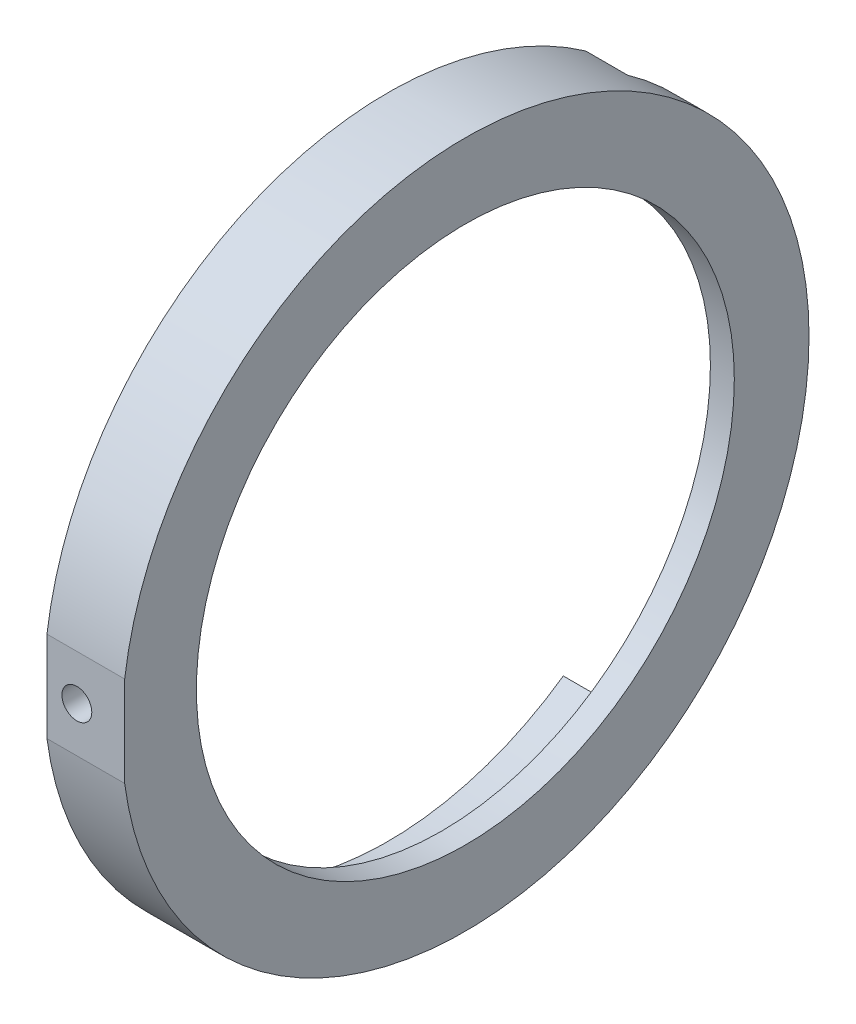
SolidWorks part; units mm, degrees
material "Stainless Steel (ferritic)"
ref_plane "Front Plane" through (0, 0, 0) normal (0, 0, 1) x (1, 0, 0)
ref_plane "Top Plane" through (0, 0, 0) normal (0, 1, 0) x (1, 0, 0)
ref_plane "Right Plane" through (0, 0, 0) normal (1, 0, 0) x (0, 0, -1)
sketch "Sketch1" plane through (0, 0, 0) normal (1, 0, 0) x (0, 0, -1)
  line L0 (-57, 7.5664) -> (-57, -7.5664)
  arc A0 (-57, -7.5664) -> (-57, 7.5664) centre (0, 0) ccw
  dimension "D1" = 115
  dimension "D2" = 57
extrude "Boss-Extrude1" add sketch "Sketch1" along normal blind 6
sketch "Sketch2" plane through (0, 0, 0) normal (-1, 0, 0) x (0, 0, 1)
  line L0 (-33.1248, -47) -> (-33.1248, 47)
  line L1 (-33.1248, 47) -> (-29.3802, 41.687)
  line L2 (-33.1248, -47) -> (-29.3802, -41.687)
  arc A1 (57, 7.5664) -> (57, -7.5664) centre (0, 0) ccw construction
  arc A2 (50.5565, 6.711) -> (50.5565, -6.711) centre (0, 0) ccw
  circle A3 centre (0, 0) radius 51
  arc M2 (57, 7.5664) -> (57, -7.5664) centre (0, 0) ccw
  line M3 (57, -7.5664) -> (57, 7.5664)
  dimension "D2" = 94
  dimension "D1" = 6.5
extrude "Boss-Extrude2" add sketch "Sketch2" along normal blind 7 contours A3 L2 L1 M2 M3
sketch "Sketch3" plane through (0, 0, 57) normal (0, 0, 1) x (1, 0, 0)
  line L0 (-7, -7.5664) -> (-7, 7.5664) construction
  circle A0 centre (-2, 0) radius 2.5
  point P4 (-7, 0)
  dimension "D1" = 5
  dimension "D2" = 5
extrude "Cut-Extrude1" cut sketch "Sketch3" against normal blind 7
sketch "Sketch4" plane through (6, 0, 0) normal (1, 0, 0) x (0, 0, -1)
  arc A2 (-44.6087, 5.9215) -> (-44.6071, -5.9338) centre (0, 0) ccw
  arc A3 (-44.6087, -5.9215) -> (-44.6087, 5.9215) centre (0, 0) ccw
  arc A4 (-44.6087, -5.9215) -> (-44.6087, 5.9215) centre (0, 0) ccw
  dimension "D1" = 12.5
extrude "Cut-Extrude2" cut sketch "Sketch4" against normal up to next contours A2 A4
sketch "Sketch5" plane through (0, 0, 0) normal (-1, 0, 0) x (0, 0, 1)
  circle A0 centre (0, 0) radius 51
extrude "Cut-Extrude3" cut sketch "Sketch5" against normal blind 2
